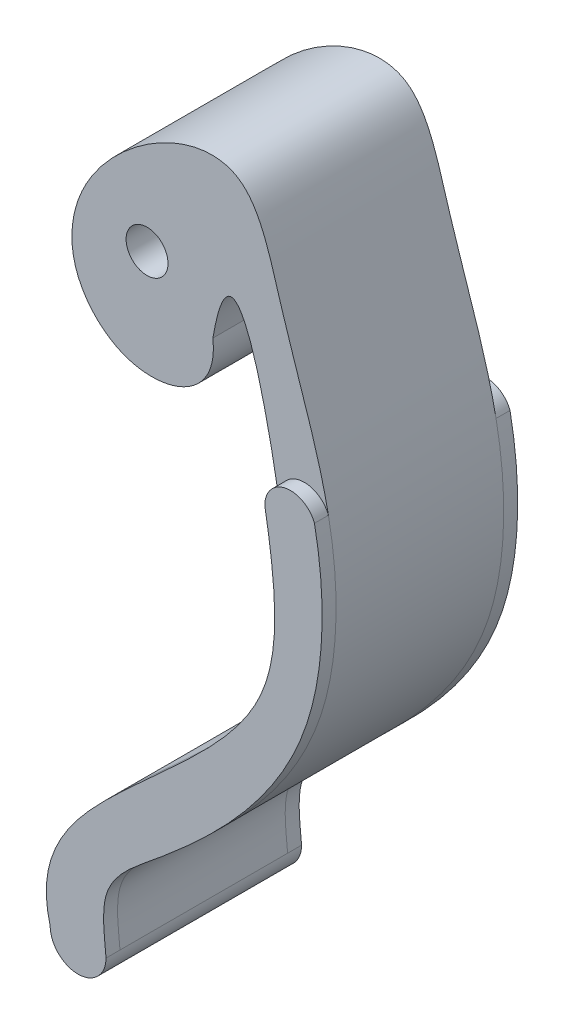
SolidWorks part; units mm, degrees
material "Rubber"
ref_plane "Front Plane" through (0, 0, 0) normal (0, 0, 1) x (1, 0, 0)
ref_plane "Top Plane" through (0, 0, 0) normal (0, 1, 0) x (1, 0, 0)
ref_plane "Right Plane" through (0, 0, 0) normal (1, 0, 0) x (0, 0, -1)
sketch "Sketch1" plane through (0, 0, 0) normal (0, 0, 1) x (1, 0, 0)
  arc A0 (-2, 0) -> (1.969, 0.3506) centre (0, 0) ccw
  spline S0 degree 3 poles (-2, 0) (-3.1409, 4.216) (2.8973, 11.4589) (14.6454, 20.2352) (14.1319, 32.4953) (10.0182, 49.404) (8.6526, 41.2663) knots 0 0 0 0 0.216145 0.503172 0.730637 1 1 1 1
  spline S1 degree 3 poles (8.6526, 41.2663) (9.1012, 37.4247) (3.2853, 35.2365) (-2.1641, 40.5398) (-0.7668, 48.9813) (10.8231, 55.5957) (13.2553, 46.3871) (15.24, 40.5538) (17.8605, 32.4215) (17.3868, 19.0552) (8.9686, 10.471) (1.345, 4.6079) (1.9022, 1.2158) (2, 0) knots 0 0 0 0 0.096764 0.147229 0.224573 0.354096 0.424864 0.483157 0.56943 0.705071 0.901237 0.95602 1 1 1 1
extrude "Boss-Extrude1" add sketch "Sketch1" along normal blind 12 contours S1 S0 A0
sketch "Sketch2" plane through (0, 0, 0) normal (0, 0, 1) x (1, 0, 0)
  arc A0 (-2, 0) -> (1.969, 0.3506) centre (0, 0) ccw
  arc A2 (17.0471, 33.7554) -> (13.4675, 33.1504) centre (15.2062, 33.7554) ccw
  spline S0 degree 3 poles (-2, 0) (-3.1409, 4.216) (2.8973, 11.4589) (14.6454, 20.2352) (14.3084, 28.2823) (13.3653, 33.7554) knots 0 0 0 0 0.216145 0.503172 0.730637 0.730637 0.730637 0.730637
  spline S1 degree 3 poles (16.9231, 34.4195) (16.9669, 34.1989) (17.771, 29.8987) (17.3868, 19.0552) (8.9686, 10.471) (1.345, 4.6079) (1.9022, 1.2158) (2, 0) knots 0.562068 0.562068 0.562068 0.562068 0.56943 0.705071 0.901237 0.95602 1 1 1 1
extrude "Boss-Extrude2" add sketch "Sketch2" against normal blind 1 contours S1 A2 S0 A0
ref_plane "Plane1" through (0, 0, 6) normal (0, 0, 1) x (1, 0, 0)
mirror "Mirror1" about plane through (0, 0, 6) normal (0, 0, 1) of "Boss-Extrude2"
sketch "Sketch3" plane through (0, 0, 12) normal (0, 0, 1) x (1, 0, 0)
  circle A0 centre (3.9374, 44.2868) radius 1.5
extrude "Cut-Extrude1" cut sketch "Sketch3" against normal blind 15 and the other way blind 1
